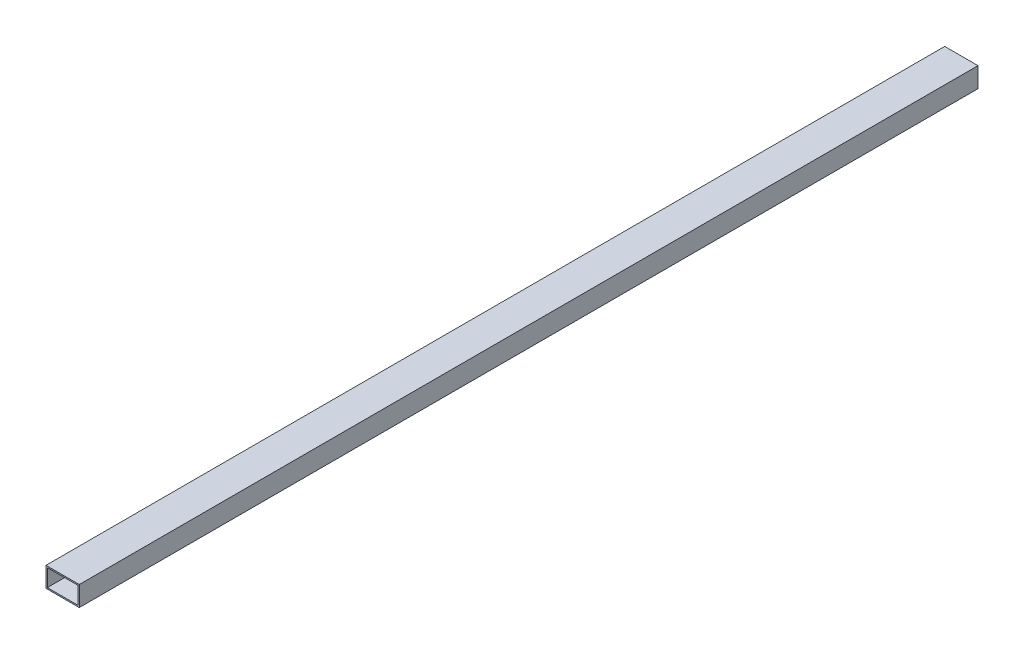
SolidWorks part; units mm, degrees
ref_plane "Přední rovina" through (0, 0, 0) normal (0, 0, 1) x (1, 0, 0)
ref_plane "Horní rovina" through (0, 0, 0) normal (0, 1, 0) x (1, 0, 0)
ref_plane "Pravá rovina" through (0, 0, 0) normal (1, 0, 0) x (0, 0, -1)
sketch "Skica1" plane through (0, 0, 0) normal (0, 0, 1) x (1, 0, 0)
  line L1 (0, 0) -> (50, 0)
  line L2 (0, 0) -> (0, 30)
  line L3 (0, 30) -> (50, 30)
  line L4 (50, 0) -> (50, 30)
  dimension "D1" = 50
  dimension "D2" = 30
extrude "Přidat vysunutím1" add sketch "Skica1" along normal blind 1350
shell "Skořepina1" thickness 2
